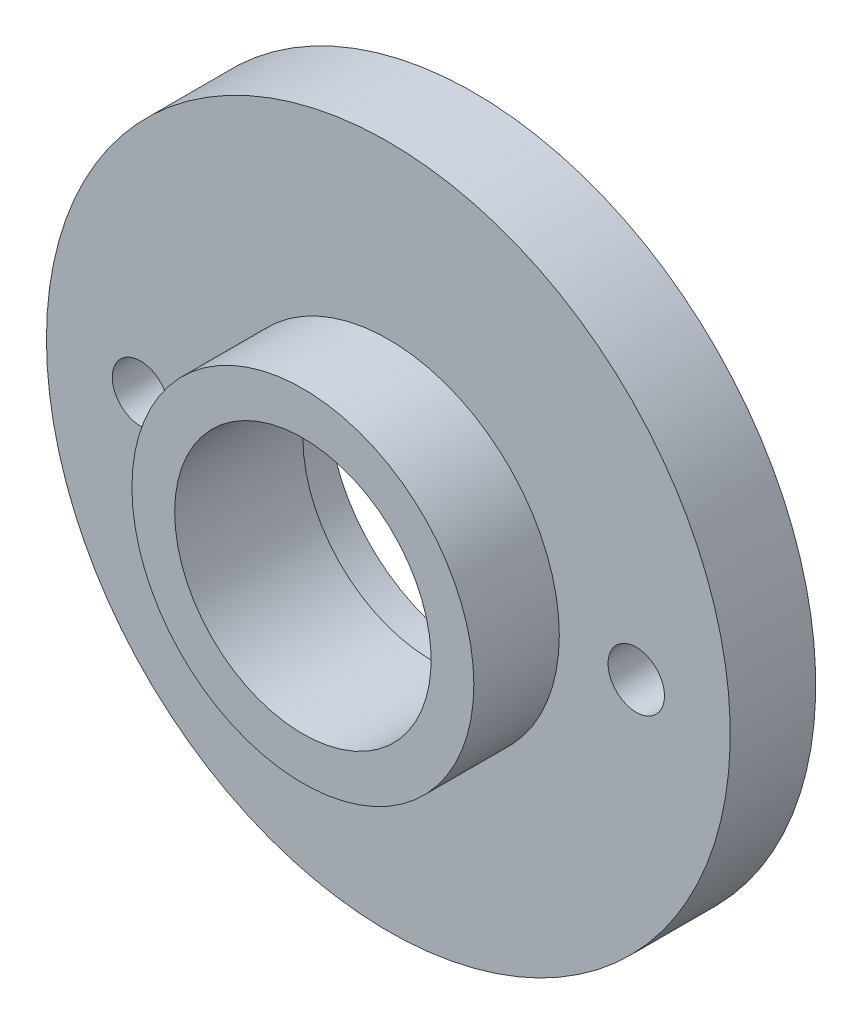
SolidWorks part; units mm, degrees
ref_plane "Front Plane" through (0, 0, 0) normal (0, 0, 1) x (1, 0, 0)
ref_plane "Top Plane" through (0, 0, 0) normal (0, 1, 0) x (1, 0, 0)
ref_plane "Right Plane" through (0, 0, 0) normal (1, 0, 0) x (0, 0, -1)
sketch "Sketch1" plane through (0, 0, 0) normal (0, 1, 0) x (1, 0, 0)
  line L0 (0, 17.3797) -> (0, -17.3797) construction
sketch "Sketch2" plane through (0, 0, 0) normal (0, 1, 0) x (1, 0, 0)
  line L0 (7.5, -5) -> (10, -5)
  line L1 (10, -5) -> (10, 0)
  line L2 (10, 0) -> (20, 0)
  line L3 (20, 0) -> (20, 5)
  line L4 (20, 5) -> (8.5, 5)
  line L5 (8.5, 5) -> (8.5, 2.5)
  line L6 (8.5, 2.5) -> (7.5, 2.5)
  line L7 (7.5, 2.5) -> (7.5, -5)
  line L8 (0, 0) -> (10, 0) construction
  line L9 (0, 200017.3797) -> (0, -200017.3797) construction
  dimension "D1" = 5
  dimension "D2" = 5
  dimension "D3" = 20
  dimension "D4" = 10
  dimension "D5" = 7.5
  dimension "D6" = 2.5
  dimension "D7" = 8.5
revolve "Revolve1" add sketch "Sketch2" angle 360 about L0
sketch "Sketch3" plane through (0, 0, 0) normal (0, 0, 1) x (1, 0, 0)
  line L0 (-20, 0) -> (-16.5, 0) construction
  line L1 (-16.5, 0) -> (-14.5, 0) construction
  line L2 (-14.5, 0) -> (-12.5, 0) construction
  line L3 (-12.5, 0) -> (12.5, 0) construction
  line L4 (12.5, 0) -> (14.5, 0) construction
  line L5 (14.5, 0) -> (16.5, 0) construction
  line L6 (16.5, 0) -> (20, 0) construction
  circle A0 centre (-14.5, 0) radius 2 construction
  circle A1 centre (14.5, 0) radius 2 construction
  circle A2 centre (0, 0) radius 20 construction
  dimension "D1" = 4
  dimension "D2" = 29
hole_wizard "M4x0.7 Tapped Hole1" positions "Sketch4" profile "Sketch5" tap size "M4x0.7" standard "ANSI Metric" end condition through all
sketch "Sketch4" plane through (0, 0, 0) normal (0, 0, 1) x (1, 0, 0)
  point P0 (-14.5, 0)
  point P3 (14.5, 0)
sketch "Sketch5" plane through (-14.5, 0, 0) normal (1, 0, 0) x (0, -1, 0)
  line L0 (0, 0) -> (0, 5)
  line L1 (0, 5) -> (1.65, 5)
  line L2 (1.65, 5) -> (1.65, 0)
  line L5 (1.65, 0) -> (0, 0)
  line L11 (0, -6.35) -> (0, 107.95) construction
  dimension "Thru Tap Drill Dia." = 3.3
  dimension "Thru Tap Drill Depth" = 5
cosmetic thread "Hole Thread1" parameters "D2"=4
cosmetic thread "Hole Thread2" parameters "D2"=4
